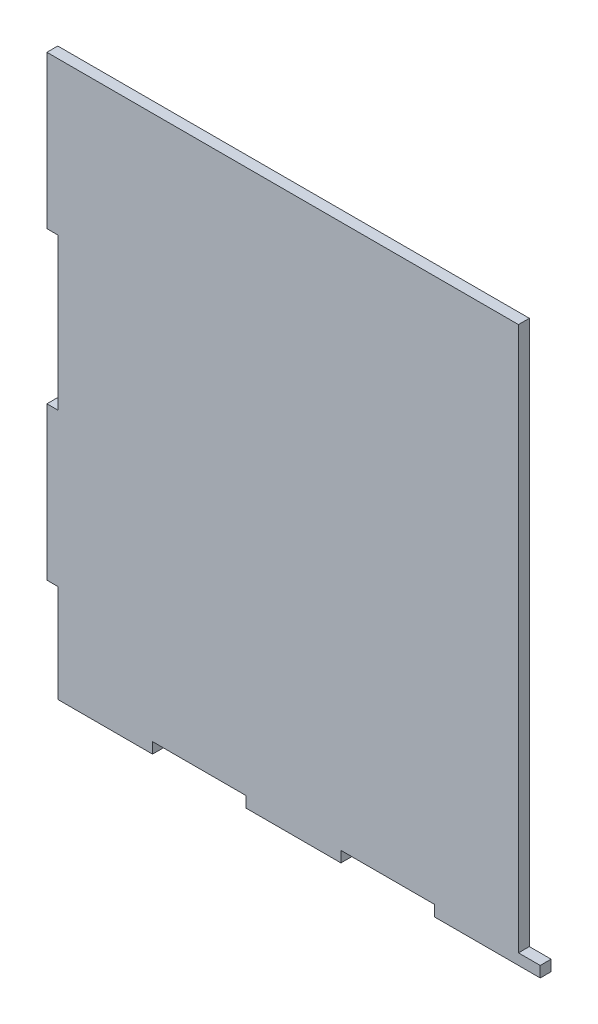
SolidWorks part; units mm, degrees
ref_plane "Front Plane" through (0, 0, 0) normal (0, 0, 1) x (1, 0, 0)
ref_plane "Top Plane" through (0, 0, 0) normal (0, 1, 0) x (1, 0, 0)
ref_plane "Right Plane" through (0, 0, 0) normal (1, 0, 0) x (0, 0, -1)
sketch "Sketch1" plane through (0, 0, 0) normal (0, 0, 1) x (1, 0, 0)
  line L0 (65.7414, 34.0484) -> (65.7414, -7.7588) construction
  line L1 (65.7414, -7.7588) -> (65.7414, -8.0588) construction
  line L2 (68.7414, -77.1445) -> (65.7414, -77.1445)
  line L3 (65.7414, -77.1445) -> (39.6214, -77.1445)
  line L4 (-12.3186, -74.1445) -> (13.5014, -74.1445) construction
  line L5 (13.5014, -74.1445) -> (13.8014, -74.1445) construction
  line L6 (65.7414, 75.8555) -> (-64.2586, -74.1445) construction
  line L7 (65.7414, -74.1445) -> (-67.2586, 75.8555) construction
  line L8 (62.7414, 75.8555) -> (62.7414, -74.1445)
  line L9 (62.7414, -74.1445) -> (68.7414, -74.1445)
  line L10 (65.7414, 34.0484) -> (62.7414, 34.0484) construction
  line L70 (65.7414, 75.8555) -> (65.7414, 34.0484)
  line L71 (65.7414, 34.0484) -> (68.7414, 34.0484)
  line L72 (68.7414, 34.0484) -> (68.7414, -8.0588)
  line L73 (68.7414, -8.0588) -> (65.7414, -8.0588)
  line L74 (65.7414, -8.0588) -> (65.7414, -49.8659)
  line L75 (65.7414, -49.8659) -> (68.7414, -49.8659)
  line L127 (39.6214, -74.1445) -> (39.6214, -77.1445)
  line L128 (-12.3186, -77.1445) -> (13.8014, -77.1445)
  line L129 (13.8014, -77.1445) -> (13.8014, -74.1445)
  line L131 (-12.3186, -74.1445) -> (-12.3186, -77.1445)
  line L132 (-64.2586, -77.1445) -> (-38.1386, -77.1445)
  line L133 (-38.1386, -77.1445) -> (-38.1386, -74.1445)
  line L136 (-38.1386, -74.1445) -> (-12.3186, -74.1445)
  line L137 (13.8014, -74.1445) -> (39.6214, -74.1445)
  line L138 (68.7414, -77.1445) -> (68.7414, -49.8659)
  line L139 (65.7414, 75.8555) -> (-67.2586, 75.8555)
  line L140 (-67.2586, 75.8555) -> (-67.2586, 33.7484)
  line L141 (-67.2586, 33.7484) -> (-64.2586, 33.7484)
  line L142 (-64.2586, 33.7484) -> (-64.2586, -8.0588)
  line L143 (-64.2586, -8.0588) -> (-67.2586, -8.0588)
  line L144 (-67.2586, -8.0588) -> (-67.2586, -50.1659)
  line L145 (-67.2586, -50.1659) -> (-64.2586, -50.1659)
  line L146 (-64.2586, -77.1445) -> (-64.2586, -50.1659)
  dimension "D1" = 153
  dimension "D2" = 42.1071
  dimension "D3" = 0.3
  dimension "D4" = 3
  dimension "D5" = 130
  dimension "D6" = 0.3
extrude "Boss-Extrude1" add sketch "Sketch1" along normal blind 3 contours L146 L132 L133 L136 L131 L128 L129 L137 L127 L3 L2 L138 L9 L8 L139 L140 L141 L142 L143 L144 L145
